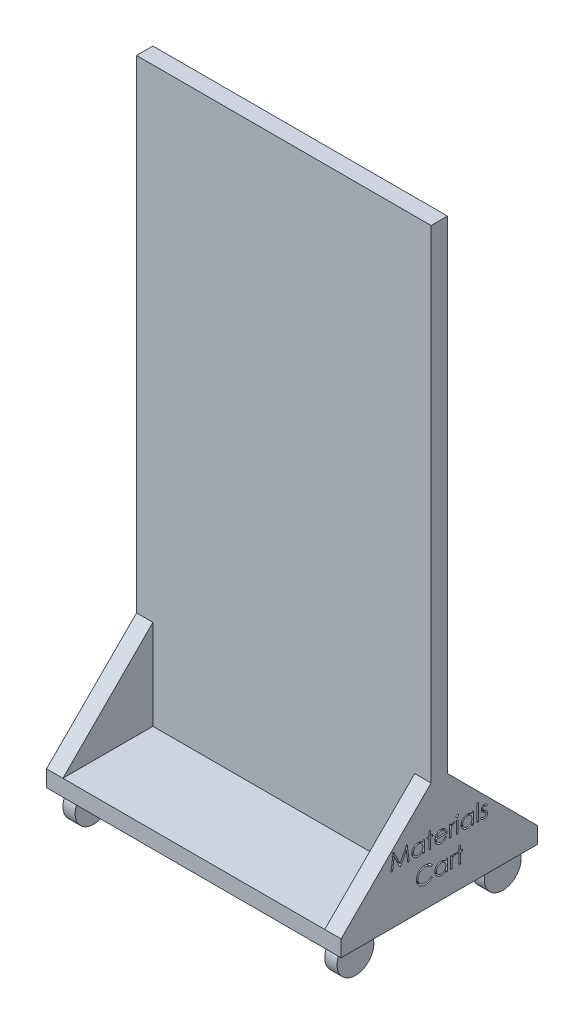
SolidWorks part; units mm, degrees
ref_plane "Front Plane" through (0, 0, 0) normal (0, 0, 1) x (1, 0, 0)
ref_plane "Top Plane" through (0, 0, 0) normal (0, 1, 0) x (1, 0, 0)
ref_plane "Right Plane" through (0, 0, 0) normal (1, 0, 0) x (0, 0, -1)
sketch "Sketch1" plane through (0, 0, 0) normal (0, 1, 0) x (1, 0, 0)
  line L1 (-457.2, -304.8) -> (457.2, -304.8)
  line L2 (-457.2, -304.8) -> (-457.2, 304.8)
  line L3 (-457.2, 304.8) -> (457.2, 304.8)
  line L4 (457.2, -304.8) -> (457.2, 304.8)
  line L5 (-457.2, -304.8) -> (457.2, 304.8) construction
  line L6 (-457.2, 304.8) -> (457.2, -304.8) construction
  point P0 (0, 0)
  dimension "D1" = 609.6
  dimension "D2" = 914.4
extrude "Boss-Extrude1" add sketch "Sketch1" along normal blind 50.8
sketch "Sketch3" plane through (0, 0, 0) normal (0, 0, 1) x (1, 0, 0)
  line L0 (457.2, 50.8) -> (457.2, 0) construction
  line L1 (-457.2, 0) -> (457.2, 0)
  line L2 (-457.2, 0) -> (-457.2, 1828.8)
  line L3 (-457.2, 1828.8) -> (457.2, 1828.8)
  line L4 (457.2, 0) -> (457.2, 1828.8)
  line L5 (-457.2, 50.8) -> (-457.2, 0) construction
  line L6 (-457.2, 0) -> (457.2, 0) construction
  dimension "D1" = 1828.8
extrude "Boss-Extrude2" add sketch "Sketch3" along normal mid plane 50.8
sketch "Sketch4" plane through (457.2, 0, 0) normal (1, 0, 0) x (0, 0, -1)
  line L0 (304.8, 0) -> (304.8, 50.8)
  line L1 (304.8, 50.8) -> (25.4, 330.2)
  line L2 (25.4, 50.8) -> (25.4, 1828.8) construction
  line L3 (25.4, 330.2) -> (-25.4, 330.2)
  line L4 (-25.4, 50.8) -> (-25.4, 1828.8) construction
  line L5 (-25.4, 330.2) -> (-304.8, 50.8)
  line L6 (-304.8, 50.8) -> (-304.8, 0)
  line L7 (-304.8, 0) -> (304.8, 0)
  line L8 (25.4, 50.8) -> (304.8, 50.8) construction
  dimension "D1" = 45
extrude "Boss-Extrude3" add sketch "Sketch4" against normal blind 50.8
mirror "Mirror1" about plane through (0, 0, 0) normal (1, 0, 0) of "Boss-Extrude3"
ref_plane "Plane1" through (406.4, 0, 0) normal (1, 0, 0) x (0, 0, -1)
sketch "Sketch5" plane through (406.4, 0, 0) normal (1, 0, 0) x (0, 0, -1)
  line L0 (-228.6, -44.45) -> (228.6, -44.45) construction
  line L1 (-304.8, 0) -> (304.8, 0) construction
  line L2 (304.8, 50.8) -> (304.8, 0) construction
  circle A0 centre (-228.6, -44.45) radius 57.15
  circle A1 centre (228.6, -44.45) radius 57.15
  point P4 (0, -44.45)
  dimension "D1" = 114.3
  dimension "D2" = 101.6
  dimension "D3" = 76.2
extrude "Boss-Extrude4" add sketch "Sketch5" along normal mid plane 38.1
mirror "Mirror2" about plane through (0, 0, 0) normal (1, 0, 0) of "Boss-Extrude4"
sketch "Sketch6" plane through (457.2, 0, 0) normal (1, 0, 0) x (0, 0, -1)
  line L0 (-203.2, 152.4) -> (203.2, 152.4) construction
  line L4 (-25.4, 330.2) -> (-304.8, 50.8) construction
  line L5 (304.8, 50.8) -> (25.4, 330.2) construction
  line L6 (-304.8, 0) -> (304.8, 0) construction
  text T0 "Materials\r\nCart" font "Century Gothic" height 50.8
  point P2 (0, 0)
  point P4 (0, 0)
  point P5 (0, 0)
  point P8 (0, 0)
  point P11 (0, 0)
  dimension "D1" = 152.4
extrude "Cut-Extrude1" cut sketch "Sketch6" against normal blind 12.7
